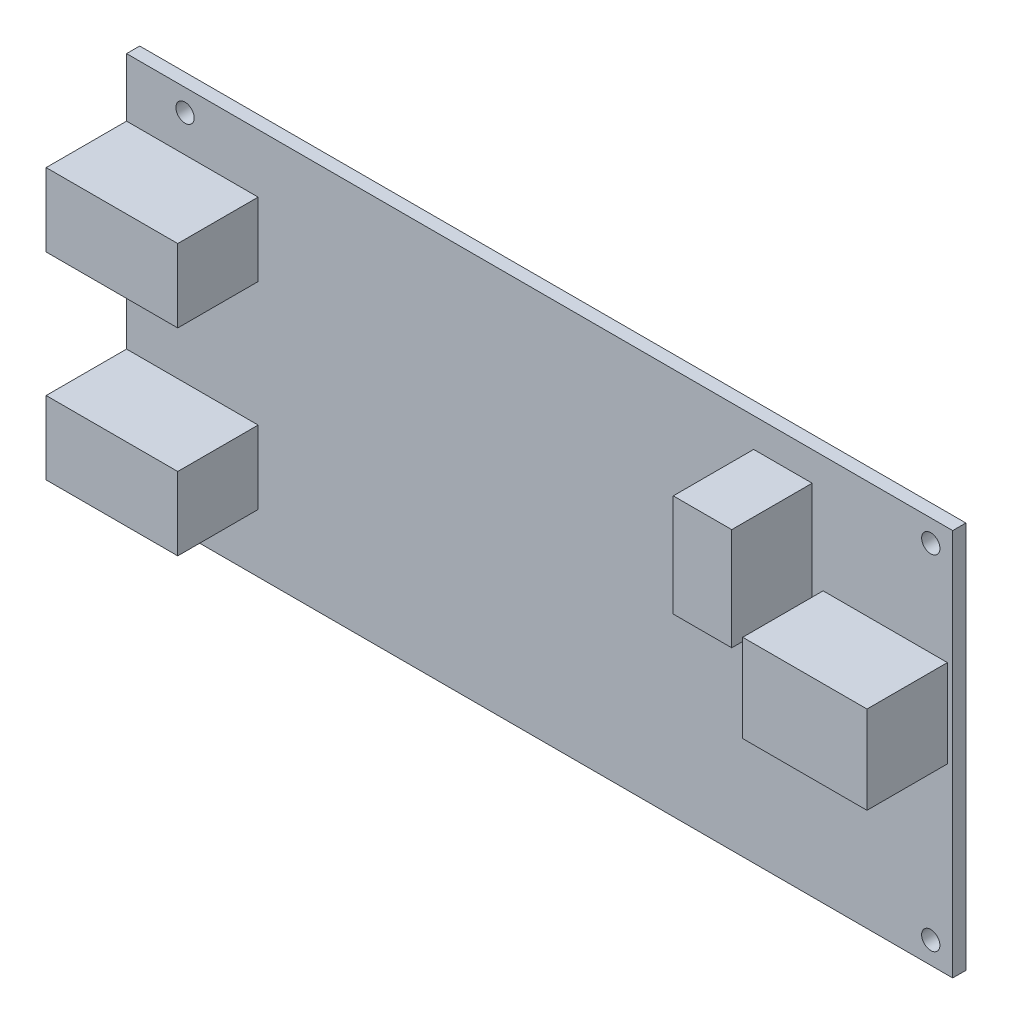
SolidWorks part; units mm, degrees
ref_plane "Front Plane" through (0, 0, 0) normal (0, 0, 1) x (1, 0, 0)
ref_plane "Top Plane" through (0, 0, 0) normal (0, 1, 0) x (1, 0, 0)
ref_plane "Right Plane" through (0, 0, 0) normal (1, 0, 0) x (0, 0, -1)
sketch "Sketch1" plane through (0, 0, 0) normal (0, 0, 1) x (1, 0, 0)
  line L1 (0, 0) -> (-113, 0)
  line L2 (0, 0) -> (0, 53)
  line L3 (0, 53) -> (-113, 53)
  line L4 (-113, 0) -> (-113, 53)
  circle A0 centre (-3, 3) radius 1.25
  circle A1 centre (-3, 50) radius 1.25
  circle A2 centre (-105, 50) radius 1.25
  circle A3 centre (-105, 3) radius 1.25
  dimension "D3" = 3
  dimension "D5" = 3
  dimension "D1" = 113
  dimension "D2" = 53
  dimension "D4" = 3
  dimension "D6" = 3
  dimension "D7" = 8
  dimension "D8" = 3
  dimension "D9" = 8
  dimension "D10" = 3
extrude "Boss-Extrude1" add sketch "Sketch1" along normal blind 1.8
sketch "Sketch2" plane through (0, 0, 1.8) normal (0, 0, 1) x (1, 0, 0)
  line L0 (0, 53) -> (-113, 53) construction
  line L1 (-17.7238, 37) -> (-0.7238, 37)
  line L2 (-17.7238, 37) -> (-17.7238, 25)
  line L3 (-17.7238, 25) -> (-0.7238, 25)
  line L4 (-0.7238, 37) -> (-0.7238, 25)
  line L5 (-113, 53) -> (-113, 0) construction
  line L6 (-19.2238, 49) -> (-27.2238, 49)
  line L7 (-19.2238, 49) -> (-19.2238, 35)
  line L8 (-19.2238, 35) -> (-27.2238, 35)
  line L9 (-27.2238, 49) -> (-27.2238, 35)
  line L10 (-113, 35) -> (-95, 35)
  line L11 (-113, 35) -> (-113, 45)
  line L12 (-113, 45) -> (-95, 45)
  line L13 (-95, 35) -> (-95, 45)
  line L14 (-113, 0) -> (0, 0) construction
  line L15 (-113, 8) -> (-95, 8)
  line L16 (-113, 8) -> (-113, 18)
  line L17 (-113, 18) -> (-95, 18)
  line L18 (-95, 8) -> (-95, 18)
  dimension "D1" = 16
  dimension "D2" = 12
  dimension "D3" = 8
  dimension "D4" = 14
  dimension "D5" = 4
  dimension "D6" = 1.5
  dimension "D7" = 17
  dimension "D8" = 10
  dimension "D9" = 8
  dimension "D10" = 18
  dimension "D11" = 10
  dimension "D12" = 8
extrude "Boss-Extrude2" add sketch "Sketch2" along normal blind 11
